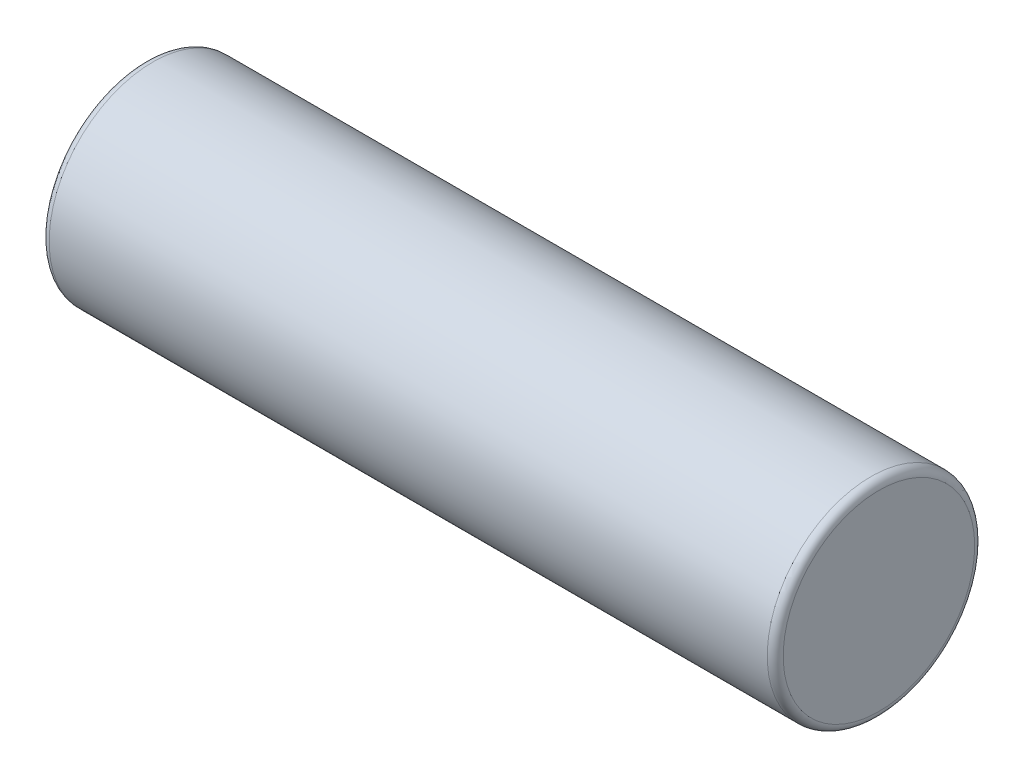
SolidWorks part; units mm, degrees
ref_plane "Спереди" through (0, 0, 0) normal (0, 0, 1) x (1, 0, 0)
ref_plane "Сверху" through (0, 0, 0) normal (0, 1, 0) x (1, 0, 0)
ref_plane "Справа" through (0, 0, 0) normal (1, 0, 0) x (0, 0, -1)
sketch "Эскиз3" plane through (0, 0, 0) normal (1, 0, 0) x (0, 0, -1)
  circle A0 centre (0, 0) radius 6.5
  dimension "D1" = 13
extrude "Бобышка-Вытянуть1" add sketch "Эскиз3" along normal blind 46
fillet "Скругление1" radius 0.5 2 edges at (46, 0, -6.5) (0, 0, -6.5)
